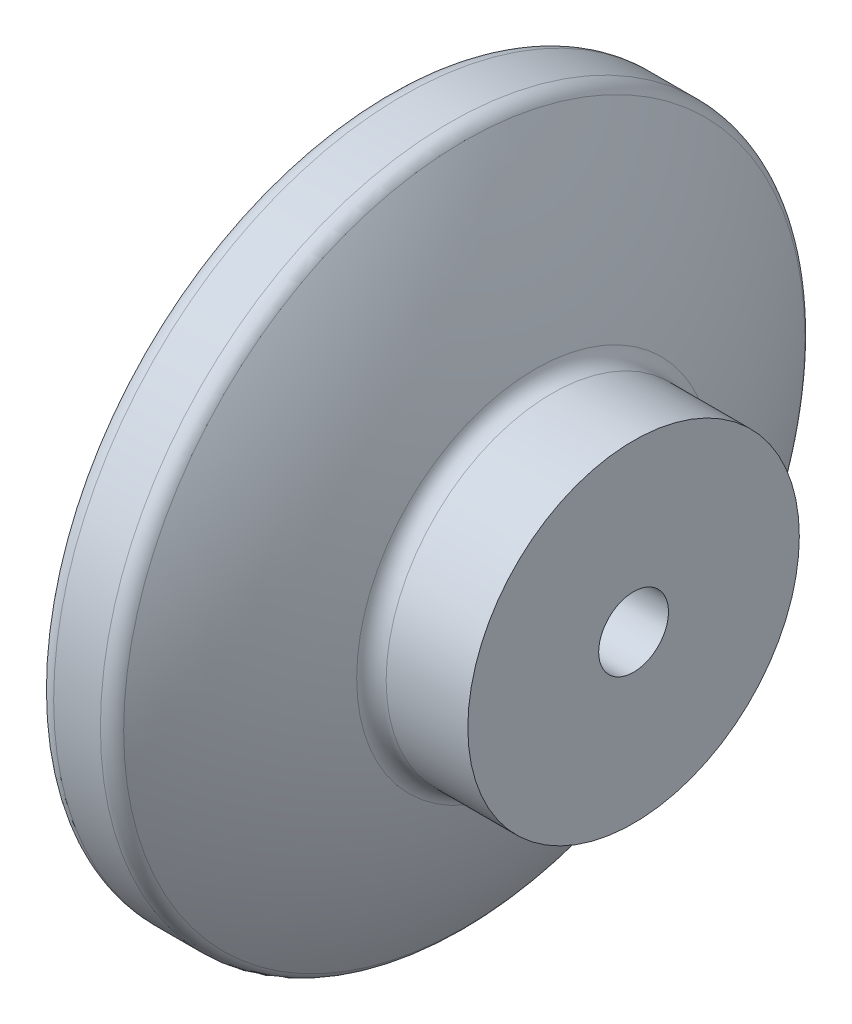
SolidWorks part; units mm, degrees
ref_plane "Front" through (0, 0, 0) normal (0, 0, 1) x (1, 0, 0)
ref_plane "Top" through (0, 0, 0) normal (0, 1, 0) x (1, 0, 0)
ref_plane "Right" through (0, 0, 0) normal (1, 0, 0) x (0, 0, -1)
sketch "ｽｹｯﾁ1" plane through (0, 0, 0) normal (0, 0, 1) x (1, 0, 0)
  line L1 (-75, 0) -> (75, 0)
  line L2 (53.4429, 4) -> (53.4429, 40)
  line L3 (53.4429, 40) -> (63.4429, 40)
  line L4 (63.4429, 4) -> (63.4429, 40)
  line L5 (63.4429, 4) -> (83.4429, 4)
  line L6 (63.4429, 4) -> (63.4429, 19)
  line L7 (63.4429, 19) -> (83.4429, 19)
  line L8 (83.4429, 4) -> (83.4429, 19)
  circle A0 centre (0, 0) radius 75
  circle A1 centre (-10, 0) radius 75
  dimension "D3" = 150
  dimension "D7" = 150
  dimension "D1" = 10
  dimension "D2" = 36
  dimension "D4" = 40
  dimension "D5" = 0
  dimension "D6" = 10
  dimension "D8" = 20
  dimension "D9" = 15
revolve "回転1" add sketch "ｽｹｯﾁ1" angle 360 about L1
fillet "ﾌｨﾚｯﾄ1" radius 2 3 edges at (72.5534, 0, 19) (63.4429, 0, 40) (53.4429, 0, 40)
sketch "ｽｹｯﾁ2" plane through (0, 0, 0) normal (1, 0, 0) x (0, 0, -1)
  circle A0 centre (0, 0) radius 8
  dimension "D1" = 16
extrude "ｶｯﾄ - 押し出し1" cut sketch "ｽｹｯﾁ2" along normal blind 70
